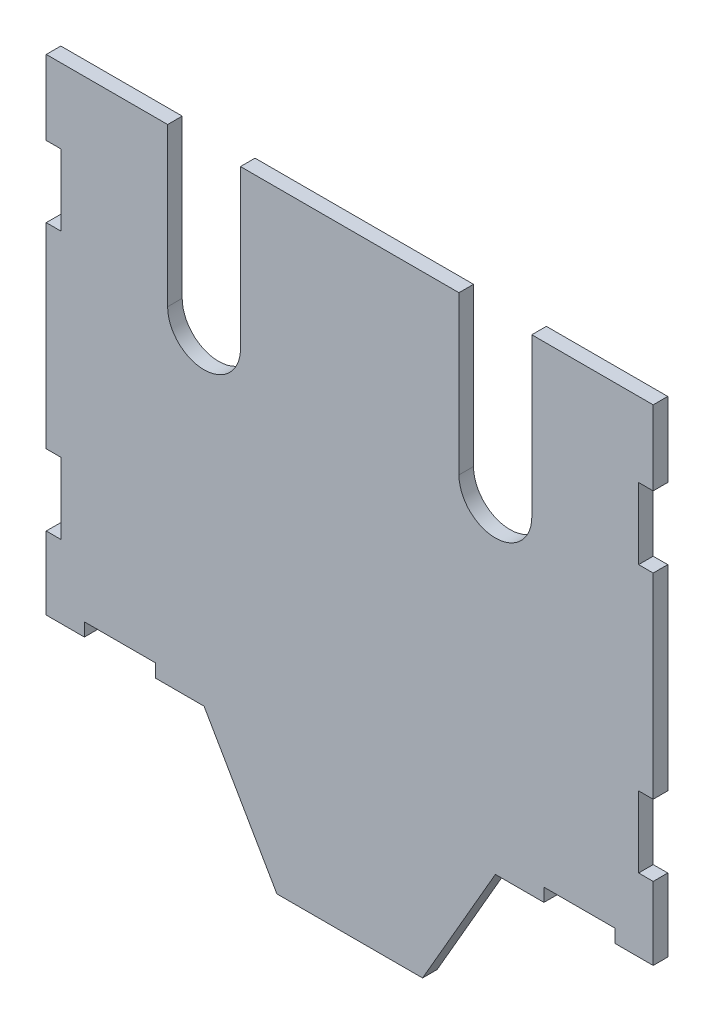
SolidWorks part; units mm, degrees
ref_plane "Спереди" through (0, 0, 0) normal (0, 0, 1) x (1, 0, 0)
ref_plane "Сверху" through (0, 0, 0) normal (0, 1, 0) x (1, 0, 0)
ref_plane "Справа" through (0, 0, 0) normal (1, 0, 0) x (0, 0, -1)
other "Configuration Table"
sketch "Эскиз1" plane through (0, 0, 0) normal (0, 0, 1) x (1, 0, 0)
  line L0 (-125, 0) -> (-125, -200) construction
  line L1 (0, 0) -> (-50, 0)
  line L2 (0, 0) -> (0, -30.7)
  line L3 (0, -200) -> (-15.7, -200)
  line L4 (-250, 0) -> (-250, -30.7)
  line L5 (-250, -100.35) -> (0, -100.35) construction
  line L6 (-250, -60) -> (-250, -140.7)
  line L7 (-250, -30.7) -> (-244, -30.7)
  line L9 (-250, -60) -> (-244, -60)
  line L10 (-244, -30.7) -> (-244, -60)
  line L11 (-250, -140.7) -> (-244, -140.7)
  line L12 (-250, -170) -> (-244, -170)
  line L13 (-244, -170) -> (-244, -140.7)
  line L14 (0, -170) -> (-6, -170)
  line L15 (-6, -170) -> (-6, -140.7)
  line L16 (0, -140.7) -> (-6, -140.7)
  line L17 (0, -60) -> (-6, -60)
  line L18 (0, -30.7) -> (-6, -30.7)
  line L19 (-6, -30.7) -> (-6, -60)
  line L20 (-250, -170) -> (-250, -200)
  line L21 (0, -170) -> (0, -200)
  line L22 (0, -60) -> (0, -140.7)
  line L23 (-15, -15) -> (-15, -115) construction
  line L24 (-235, -15) -> (-135, -15) construction
  line L25 (-235, -15) -> (-235, -115) construction
  line L26 (-235, -115) -> (-135, -115) construction
  line L27 (-135, -15) -> (-135, -115) construction
  line L28 (-15, -115) -> (-115, -115) construction
  line L29 (-115, -15) -> (-115, -115) construction
  line L30 (-15, -15) -> (-115, -15) construction
  line L31 (-185, -15) -> (-185, -115) construction
  line L32 (-65, -15) -> (-65, -115) construction
  line L33 (-200, -65) -> (-200, 0)
  line L34 (-170, -65) -> (-170, 0)
  line L35 (-200, 0) -> (-250, 0)
  line L36 (-80, -65) -> (-80, 0)
  line L37 (-50, -65) -> (-50, 0)
  line L38 (-80, 0) -> (-170, 0)
  line L39 (-185, -200) -> (-205, -200)
  line L40 (-155, -251.9615) -> (-95, -251.9615)
  line L41 (-95, -251.9615) -> (-65, -200)
  line L45 (-185, -200) -> (-155, -251.9615)
  line L46 (-125, -148.0385) -> (-155, -148.0385) [skipped]
  line L47 (-170, -174.0192) -> (-185, -200) [skipped]
  line L48 (-65, -200) -> (-80, -174.0192) [skipped]
  line L49 (-234.3, -200) -> (-250, -200)
  line L51 (-234.3, -200) -> (-234.3, -194.55)
  line L52 (-234.3, -194.55) -> (-205, -194.55)
  line L53 (-205, -200) -> (-205, -194.55)
  line L54 (-15.7, -200) -> (-15.7, -194.55)
  line L55 (-15.7, -194.55) -> (-45, -194.55)
  line L56 (-45, -200) -> (-45, -194.55)
  line L57 (-45, -200) -> (-65, -200)
  arc A0 (-200, -65) -> (-170, -65) centre (-185, -65) ccw
  arc A1 (-50, -65) -> (-80, -65) centre (-65, -65) cw
  circle A2 centre (-125, -200) radius 51.9615 construction
  dimension "D10" = 30
  dimension "D1" = 250
  dimension "D2" = 200
  dimension "D3" = 6
  dimension "D4" = 29.3
  dimension "D5" = 30.7
  dimension "D6" = 30
  dimension "D7" = 15
  dimension "D8" = 15
  dimension "D9" = 100
  dimension "D11" = 50
  dimension "D12" = 60
  dimension "D13" = 29.3
  dimension "D14" = 5.45
  dimension "D15" = 15.7
extrude "Бобышка-Вытянуть1" add sketch "Эскиз1" along normal blind 6
